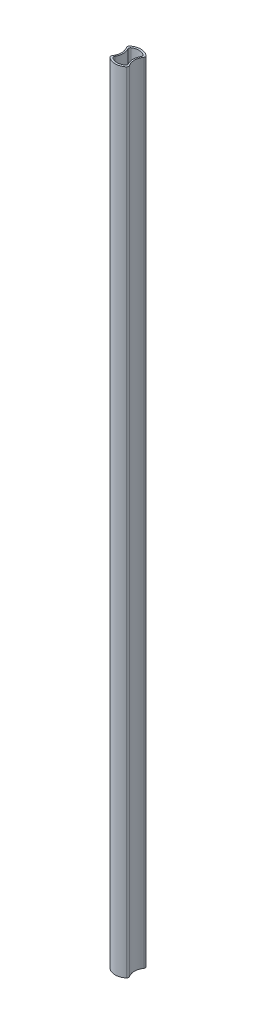
SolidWorks part; units mm, degrees
material "1060 Alloy"
ref_plane "Front Plane" through (0, 0, 0) normal (0, 0, 1) x (1, 0, 0)
ref_plane "Top Plane" through (0, 0, 0) normal (0, 1, 0) x (1, 0, 0)
ref_plane "Right Plane" through (0, 0, 0) normal (1, 0, 0) x (0, 0, -1)
sketch "Sketch1" plane through (0, 0, 0) normal (0, 1, 0) x (1, 0, 0)
  line L1 (0, -55) -> (0, 55) construction
  arc A0 (-4.1856, -4.973) -> (4.1856, -4.973) centre (0, 0) ccw
  arc A1 (-4.3694, -3.6469) -> (-4.3694, 3.6469) centre (-9.75, 0) ccw
  arc A2 (4.3694, 3.6469) -> (4.3694, -3.6469) centre (9.75, 0) ccw
  arc A3 (4.1856, 4.973) -> (-4.1856, 4.973) centre (0, 0) ccw
  arc A4 (-4.1856, -4.973) -> (-4.3694, -3.6469) centre (-3.5417, -4.2079) cw
  arc A5 (4.3694, -3.6469) -> (4.1856, -4.973) centre (3.5417, -4.2079) cw
  arc A6 (4.3694, 3.6469) -> (4.1856, 4.973) centre (3.5417, 4.2079) ccw
  arc A7 (-4.1856, 4.973) -> (-4.3694, 3.6469) centre (-3.5417, 4.2079) ccw
  arc A8 (-3.0556, -4.5731) -> (3.0556, -4.5731) centre (0, 0) ccw
  arc A9 (-3.3667, -3.2428) -> (-3.3667, 3.2428) centre (-9, 0) ccw
  arc A11 (-3.3667, 3.2428) -> (-3.0556, 4.5731) centre (-2.5, 3.7417) cw
  arc A12 (3.0556, 4.5731) -> (-3.0556, 4.5731) centre (0, 0) ccw
  arc A13 (3.3667, 3.2428) -> (3.3667, -3.2428) centre (9, 0) ccw
  arc A14 (3.0556, 4.5731) -> (3.3667, 3.2428) centre (2.5, 3.7417) cw
  arc A15 (3.3667, -3.2428) -> (3.0556, -4.5731) centre (2.5, -3.7417) cw
  arc A16 (-3.3667, -3.2428) -> (-3.0556, -4.5731) centre (-2.5, -3.7417) ccw
  point P16 (4.875, 4.2993)
  dimension "D1" = 1
  dimension "D2" = 1
extrude "Boss-Extrude1" add sketch "Sketch1" along normal blind 400
